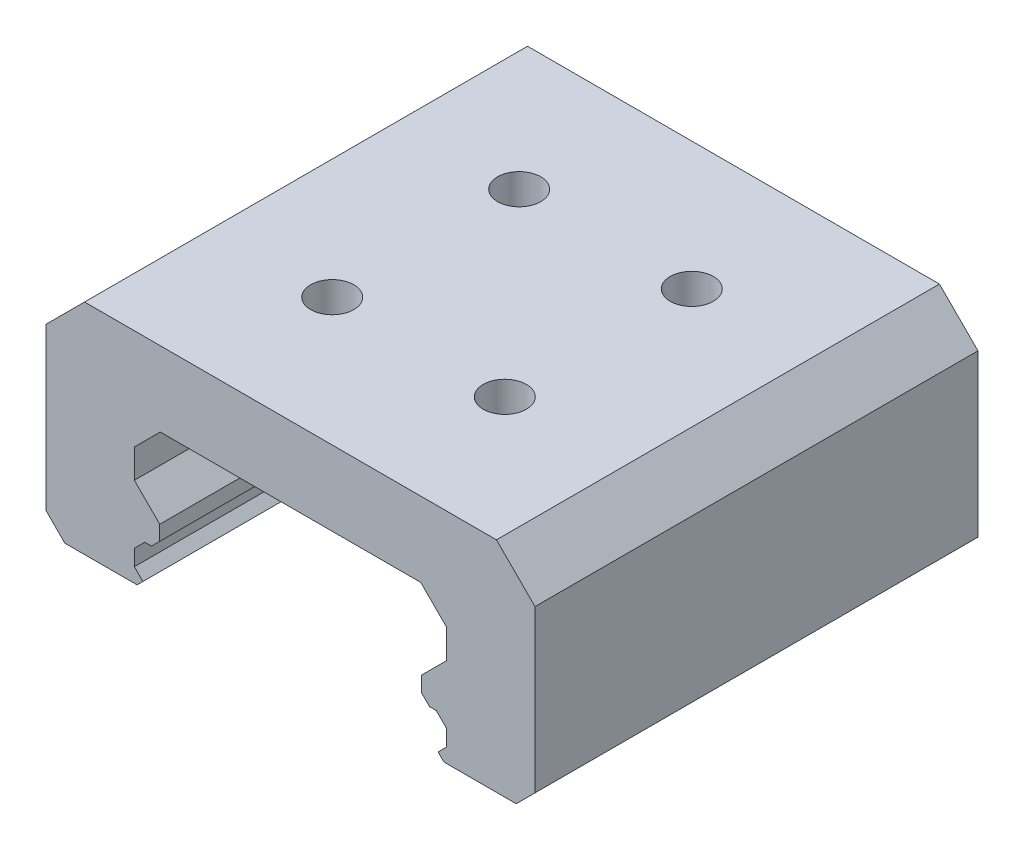
SolidWorks part; units mm, degrees
ref_plane "前视基准面" through (0, 0, 0) normal (0, 0, 1) x (1, 0, 0)
ref_plane "上视基准面" through (0, 0, 0) normal (0, 1, 0) x (1, 0, 0)
ref_plane "右视基准面" through (0, 0, 0) normal (1, 0, 0) x (0, 0, -1)
sketch "Sketch1" plane through (0, 0, 0) normal (0, 0, 1) x (1, 0, 0)
  line L24 (-9.0549, 5.7851) -> (9.0549, 5.7851)
  line L35 (-10.8561, -3.2254) -> (-10.2614, -3.8202)
  line L36 (-10.8561, -2.1135) -> (-10.8561, -3.2254)
  line L37 (-10.1346, -1.392) -> (-10.8561, -2.1135)
  line L38 (-9.6666, -1.392) -> (-10.1346, -1.392)
  line L39 (-9.0919, -0.8173) -> (-9.6666, -1.392)
  line L40 (-9.0919, 0.2129) -> (-9.0919, -0.8173)
  line L41 (-10.8561, 1.9772) -> (-9.0919, 0.2129)
  line L42 (-10.8561, 3.9838) -> (-10.8561, 1.9772)
  line L43 (-9.0549, 5.7851) -> (-10.8561, 3.9838)
  line L46 (14.3201, 10.9812) -> (-14.3201, 10.9812)
  line L47 (-14.3201, 10.9812) -> (-17, 8.3013)
  line L48 (-17, 8.3013) -> (-17, -2.9179)
  line L49 (-17, -2.9179) -> (-15.6924, -4.2255)
  line L55 (-10.2614, -3.8202) -> (-10.6667, -4.2255)
  line L56 (-10.6667, -4.2255) -> (-15.6924, -4.2255)
  line L59 (0, 5.7851) -> (0, 10.9812) construction
  line L60 (10.6667, -4.2255) -> (15.6924, -4.2255)
  line L61 (10.2614, -3.8202) -> (10.6667, -4.2255)
  line L62 (17, -2.9179) -> (15.6924, -4.2255)
  line L63 (17, 8.3013) -> (17, -2.9179)
  line L64 (14.3201, 10.9812) -> (17, 8.3013)
  line L65 (9.0549, 5.7851) -> (10.8561, 3.9838)
  line L66 (10.8561, 3.9838) -> (10.8561, 1.9772)
  line L67 (10.8561, 1.9772) -> (9.0919, 0.2129)
  line L68 (9.0919, 0.2129) -> (9.0919, -0.8173)
  line L69 (9.0919, -0.8173) -> (9.6666, -1.392)
  line L70 (9.6666, -1.392) -> (10.1346, -1.392)
  line L71 (10.1346, -1.392) -> (10.8561, -2.1135)
  line L72 (10.8561, -2.1135) -> (10.8561, -3.2254)
  line L73 (10.8561, -3.2254) -> (10.2614, -3.8202)
  dimension "D1" = 17
extrude "Boss-Extrude1" add sketch "Sketch1" along normal blind 30.8
sketch "Sketch2" plane through (0, 10.9812, 0) normal (0, 1, 0) x (1, 0, 0)
  line L0 (14.3201, 0) -> (-14.3201, 0) construction
  circle A0 centre (-6, -8.9) radius 1.5
  circle A1 centre (6, -8.9) radius 1.5
  circle A2 centre (6, -21.9) radius 1.5
  circle A3 centre (-6, -21.9) radius 1.5
  dimension "D1" = 3
  dimension "D2" = 8.9
  dimension "D3" = 13
  dimension "D4" = 6
  dimension "D5" = 12
  dimension "D6" = 3
  dimension "D7" = 3
  dimension "D8" = 3
extrude "Cut-Extrude1" cut sketch "Sketch2" against normal blind 3
